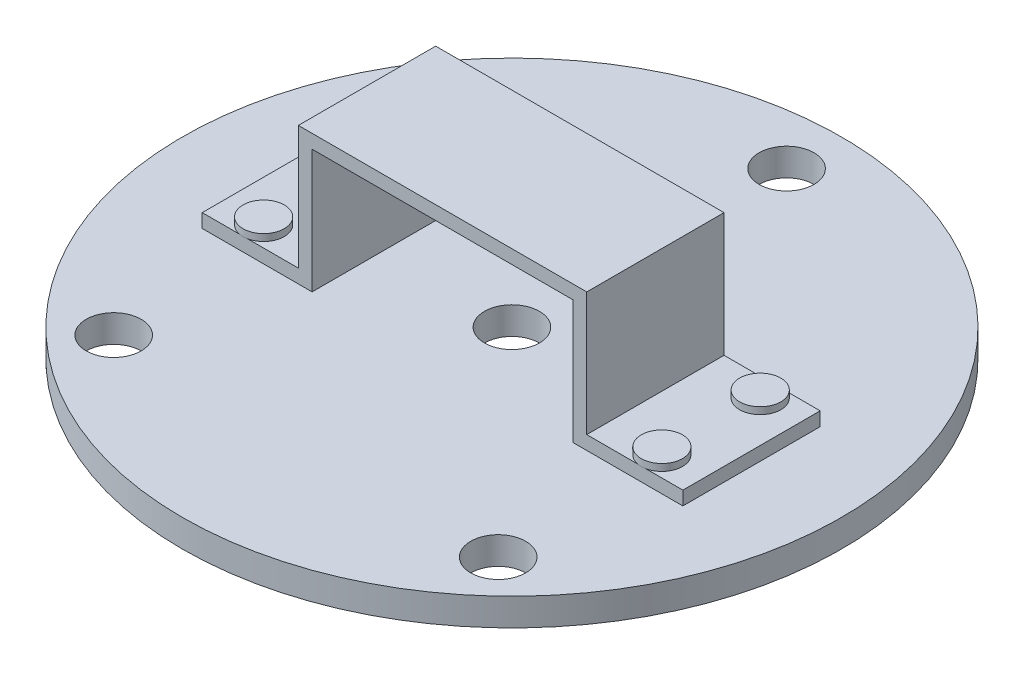
SolidWorks part; units mm, degrees
ref_plane "Front Plane" through (0, 0, 0) normal (0, 0, 1) x (1, 0, 0)
ref_plane "Top Plane" through (0, 0, 0) normal (0, 1, 0) x (1, 0, 0)
ref_plane "Right Plane" through (0, 0, 0) normal (1, 0, 0) x (0, 0, -1)
sketch "Sketch1" plane through (0, 0, 0) normal (0, 1, 0) x (1, 0, 0)
  circle A0 centre (0, 0) radius 120
  dimension "D1" = 240
extrude "Boss-Extrude1" add sketch "Sketch1" along normal blind 10
sketch "Sketch2" plane through (0, 10, 0) normal (0, 1, 0) x (1, 0, 0)
  circle A0 centre (0, 0) radius 10
  dimension "D1" = 20
extrude "Cut-Extrude1" cut sketch "Sketch2" against normal through all both and the other way through all
sketch "Sketch3" plane through (0, 10, 0) normal (0, 1, 0) x (1, 0, 0)
  line L0 (0, -5.5) -> (0, 5.5) construction
  circle A0 centre (0, 100) radius 10
  circle A1 centre (-70, -75) radius 10
  circle A2 centre (0, 0) radius 120 construction
  circle A3 centre (70, -75) radius 10
  dimension "D1" = 20
  dimension "D6" = 20
  dimension "D2" = 100
  dimension "D3" = 70
  dimension "D4" = 75
  dimension "D5" = 175
extrude "Cut-Extrude2" cut sketch "Sketch3" against normal through all both
sketch "Sketch8" plane through (0, 10, 0) normal (0, 1, 0) x (1, 0, 0)
  line L1 (-87.5, -25.2624) -> (-52.5, -25.2624)
  line L2 (-87.5, -25.2624) -> (-87.5, 24.7376)
  line L3 (-87.5, 24.7376) -> (-52.5, 24.7376)
  line L4 (-52.5, -25.2624) -> (-52.5, 24.7376)
  line L5 (-87.5, -25.2624) -> (-52.5, 24.7376) construction
  line L6 (-87.5, 24.7376) -> (-52.5, -25.2624) construction
  point P0 (-70, -0.2624)
  dimension "D1" = 50
  dimension "D2" = 35
  dimension "D3" = 70
extrude "Boss-Extrude3" add sketch "Sketch8" along normal blind 5
mirror "Mirror2" about plane through (0, 0, 0) normal (1, 0, 0) of "Boss-Extrude3"
sketch "Sketch9" plane through (-52.5, 0, 0) normal (1, 0, 0) x (0, 0, -1)
  line L1 (-25.2624, 10) -> (24.7376, 10)
  line L2 (-25.2624, 10) -> (-25.2624, 55)
  line L3 (-25.2624, 55) -> (24.7376, 55)
  line L4 (24.7376, 10) -> (24.7376, 55)
  dimension "D1" = 45
  dimension "D2" = 50
extrude "Boss-Extrude4" add sketch "Sketch9" along normal blind 5
mirror "Mirror3" about plane through (0, 0, 0) normal (1, 0, 0) of "Boss-Extrude4"
sketch "Sketch10" plane through (0, 55, 0) normal (0, 1, 0) x (1, 0, 0)
  line L1 (-52.5, 24.7376) -> (52.5, 24.7376)
  line L2 (-52.5, 24.7376) -> (-52.5, -25.2624)
  line L3 (-52.5, -25.2624) -> (52.5, -25.2624)
  line L4 (52.5, 24.7376) -> (52.5, -25.2624)
extrude "Boss-Extrude5" add sketch "Sketch10" along normal blind 5
sketch "Sketch11" plane through (0, 15, 0) normal (0, 1, 0) x (1, 0, 0)
  line L0 (-87.5, 24.7376) -> (-87.5, -25.2624) construction
  circle A0 centre (-72.5, 17.9049) radius 5
  circle A1 centre (-72.5, -16.9707) radius 5
  dimension "D1" = 10
  dimension "D2" = 10
  dimension "D3" = 15
  dimension "D4" = 15
extrude "Cut-Extrude3" cut sketch "Sketch11" against normal through all both and the other way through all
mirror "Mirror4" about plane through (0, 0, 0) normal (1, 0, 0) of "Cut-Extrude3"
sketch "Sketch12" plane through (0, 15, 0) normal (0, 1, 0) x (1, 0, 0)
  line L0 (-33, 0) -> (33, 0) construction
  circle A0 centre (-72.5, 17.9049) radius 7.5
  circle A1 centre (-72.5, -17.9049) radius 7.5
  dimension "D1" = 15
extrude "Boss-Extrude6" add sketch "Sketch12" along normal blind 2.5
mirror "Mirror5" about plane through (0, 0, 0) normal (1, 0, 0) of "Boss-Extrude6"
